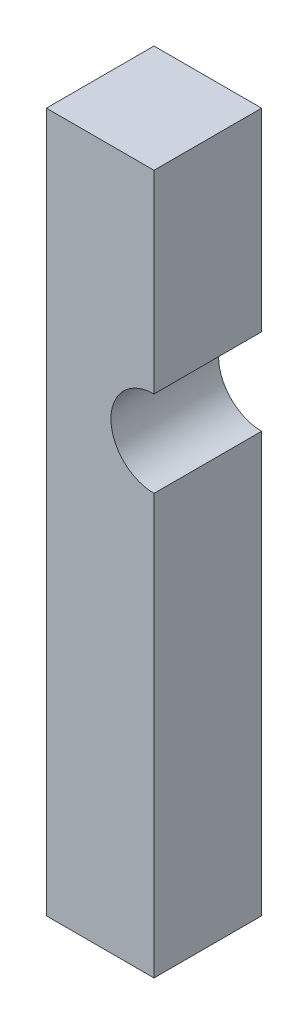
SolidWorks part; units mm, degrees
material "Balsa"
ref_plane "Alzado" through (0, 0, 0) normal (0, 0, 1) x (1, 0, 0)
ref_plane "Planta" through (0, 0, 0) normal (0, 1, 0) x (1, 0, 0)
ref_plane "Vista lateral" through (0, 0, 0) normal (1, 0, 0) x (0, 0, -1)
sketch "Croquis1" plane through (0, 0, 0) normal (0, 1, 0) x (1, 0, 0)
  line L1 (-2.5, -2.5) -> (2.5, -2.5)
  line L2 (-2.5, -2.5) -> (-2.5, 2.5)
  line L3 (-2.5, 2.5) -> (2.5, 2.5)
  line L4 (2.5, -2.5) -> (2.5, 2.5)
  line L5 (-2.5, -2.5) -> (2.5, 2.5) construction
  line L6 (-2.5, 2.5) -> (2.5, -2.5) construction
  point P0 (0, 0)
  dimension "D1" = 5
  dimension "D2" = 5
extrude "Saliente-Extruir1" add sketch "Croquis1" along normal mid plane 32.5
sketch "Croquis2" plane through (0, 0, 2.5) normal (0, 0, 1) x (1, 0, 0)
  line L0 (2.5, 16.25) -> (2.5, 5.25) construction
  line L1 (2.5, 16.25) -> (2.5, -16.25) construction
  circle A0 centre (2.5, 5.25) radius 2
  dimension "D2" = 4
  dimension "D1" = 11
extrude "Cortar-Extruir1" cut sketch "Croquis2" against normal through all
